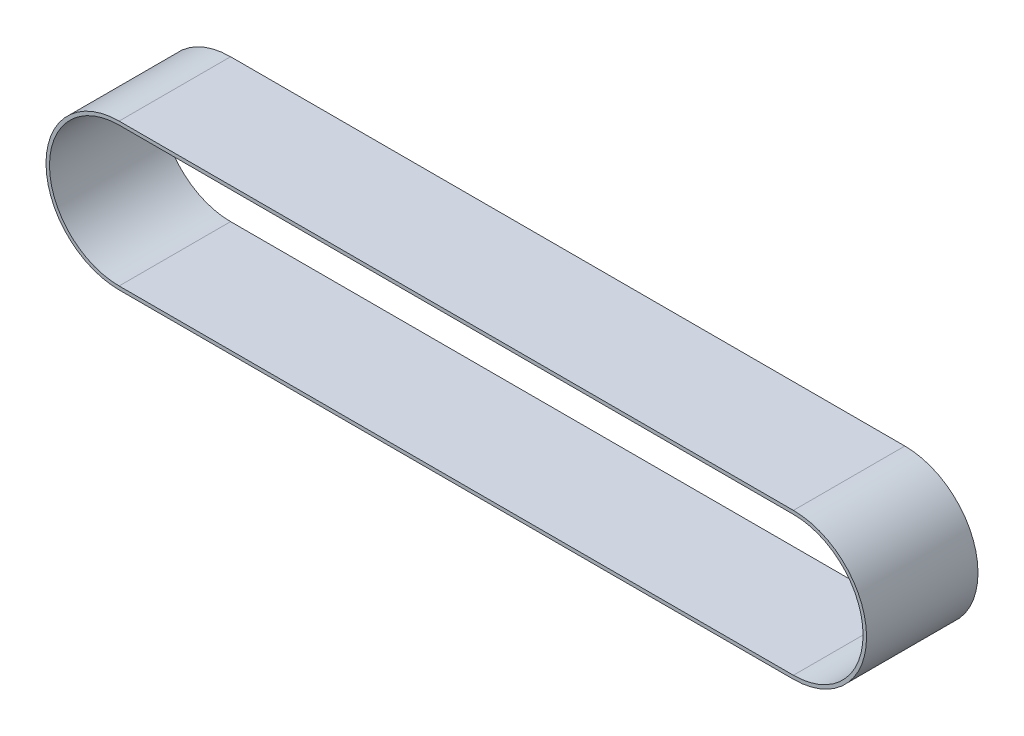
SolidWorks part; units mm, degrees
material "POLYURETHANE (11671)"
ref_plane "Front Plane" through (0, 0, 0) normal (0, 0, 1) x (1, 0, 0)
ref_plane "Top Plane" through (0, 0, 0) normal (0, 1, 0) x (1, 0, 0)
ref_plane "Right Plane" through (0, 0, 0) normal (1, 0, 0) x (0, 0, -1)
sketch "Sketch1" plane through (0, 0, 0) normal (0, 0, 1) x (1, 0, 0)
  line L0 (0, 0) -> (307.34, 0) construction
  line L1 (0, 31.75) -> (307.34, 31.75)
  line L2 (0, -31.75) -> (307.34, -31.75)
  line L3 (0, 0) -> (307.34, 0) construction
  line L4 (0, 33.3375) -> (307.34, 33.3375)
  line L5 (0, -33.3375) -> (307.34, -33.3375)
  arc A0 (0, 31.75) -> (0, -31.75) centre (0, 0) ccw
  arc A1 (307.34, -31.75) -> (307.34, 31.75) centre (307.34, 0) ccw
  arc A2 (0, 33.3375) -> (0, -33.3375) centre (0, 0) ccw
  arc A3 (307.34, -33.3375) -> (307.34, 33.3375) centre (307.34, 0) ccw
  point P3 (153.67, 0)
  point P10 (153.67, 0)
  dimension "D2" = 63.5
  dimension "D3" = 66.675
  dimension "D1" = 307.34
extrude "Boss-Extrude1" add sketch "Sketch1" along normal blind 50.8
